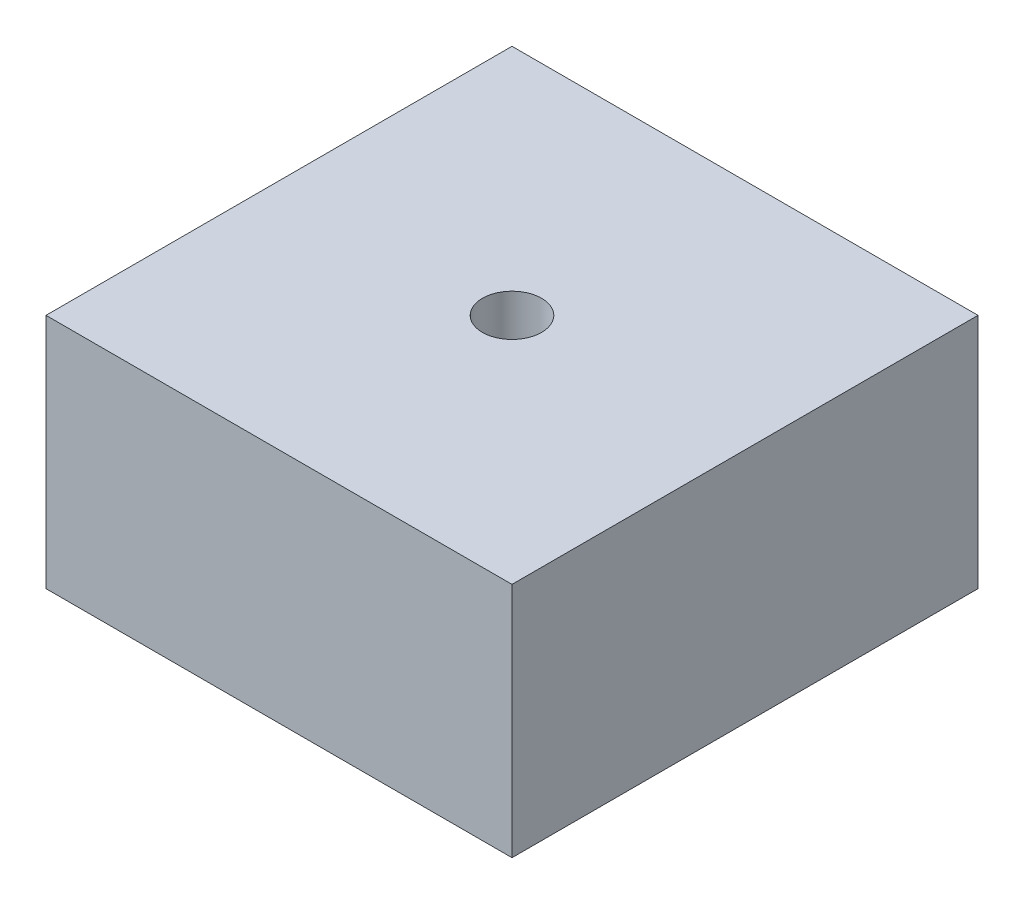
SolidWorks part; units mm, degrees
ref_plane "Front Plane" through (0, 0, 0) normal (0, 0, 1) x (1, 0, 0)
ref_plane "Top Plane" through (0, 0, 0) normal (0, 1, 0) x (1, 0, 0)
ref_plane "Right Plane" through (0, 0, 0) normal (1, 0, 0) x (0, 0, -1)
other "Default"
sketch "Sketch1" plane through (0, 0, 0) normal (0, 1, 0) x (1, 0, 0)
  line L1 (-12.5, 12.5) -> (12.5, 12.5)
  line L2 (-12.5, 12.5) -> (-12.5, -12.5)
  line L3 (-12.5, -12.5) -> (12.5, -12.5)
  line L4 (12.5, 12.5) -> (12.5, -12.5)
  line L5 (-12.5, 12.5) -> (12.5, -12.5) construction
  line L6 (-12.5, -12.5) -> (12.5, 12.5) construction
  point P0 (0, 0)
  dimension "Size" = 25
extrude "Boss-Extrude1" add sketch "Sketch1" along normal mid plane 12.7
sketch "Sketch2" plane through (0, 6.35, 0) normal (0, 1, 0) x (1, 0, 0)
  circle A0 centre (0, 0) radius 1.5875
  dimension "HoleSize" = 3.175
extrude "Hole" cut sketch "Sketch2" against normal through all
